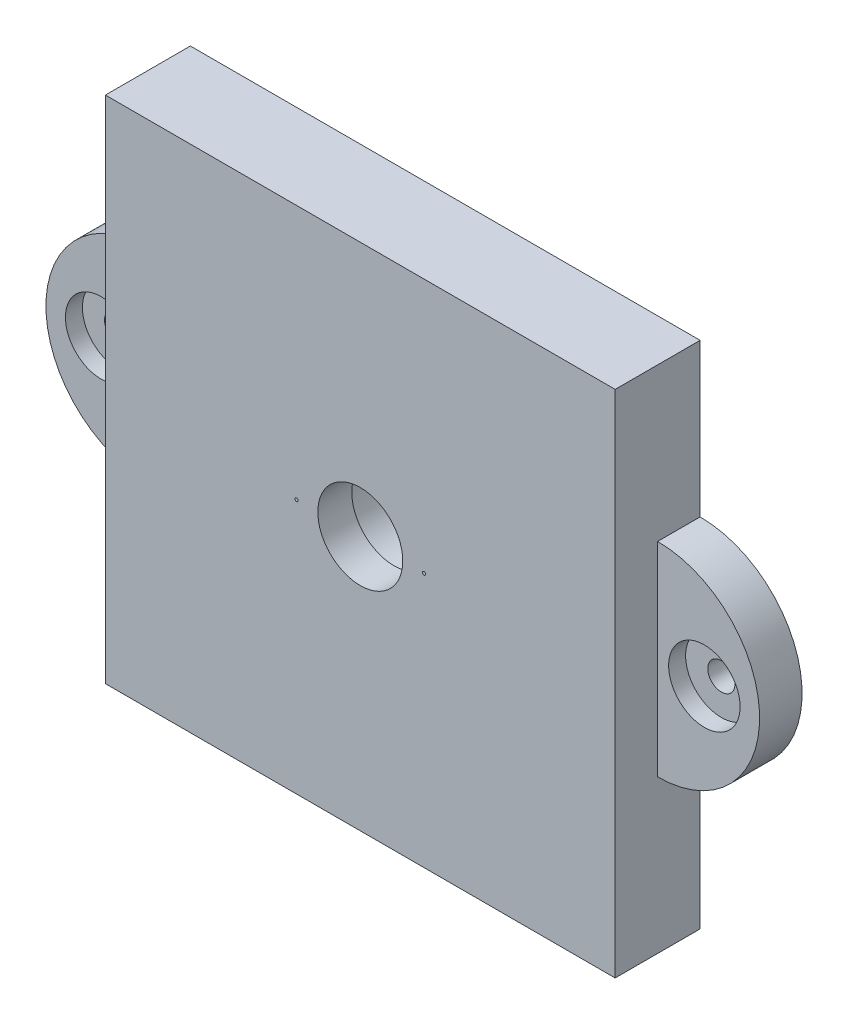
SolidWorks part; units mm, degrees
ref_plane "Plan de face" through (0, 0, 0) normal (0, 0, 1) x (1, 0, 0)
ref_plane "Plan de dessus" through (0, 0, 0) normal (0, 1, 0) x (1, 0, 0)
ref_plane "Plan de droite" through (0, 0, 0) normal (1, 0, 0) x (0, 0, -1)
sketch "Esquisse1" plane through (0, 0, 0) normal (0, 0, 1) x (1, 0, 0)
  line L1 (-30.7513, 21.8422) -> (1.2487, 21.8422)
  line L2 (-30.7513, 21.8422) -> (-30.7513, 3.8422)
  line L3 (-30.7513, -38.1578) -> (29.2487, -38.1578)
  line L4 (29.2487, 21.8422) -> (29.2487, 3.8422)
  line L5 (1.2487, 21.8422) -> (29.2487, 21.8422)
  line L8 (29.2487, -20.1578) -> (29.2487, -38.1578)
  line L9 (-30.7513, -20.1578) -> (-30.7513, -38.1578)
  arc A1 (29.2487, 3.8422) -> (29.2487, -20.1578) centre (29.2487, -8.1578) cw
  arc A2 (-30.7513, -20.1578) -> (-30.7513, 3.8422) centre (-30.7513, -8.1578) cw
  dimension "D3" = 18
  dimension "D7" = 12
  dimension "D4" = 12
  dimension "D1" = 60
  dimension "D2" = 60
  dimension "D5" = 18
  dimension "D6" = 28
extrude "Boss.-Extru.1" add sketch "Esquisse1" along normal blind 10
sketch "Esquisse2" plane through (0, 0, 10) normal (0, 0, 1) x (1, 0, 0)
  line L5 (29.2487, 21.8422) -> (-30.7513, 21.8422) construction
  line L10 (29.2487, -38.1578) -> (29.2487, -20.1578) construction
  circle A0 centre (-0.7513, -8.1578) radius 5
  dimension "D1" = 30
  dimension "D2" = 30
  dimension "D3" = 10
extrude "Enlèv. mat.-Extru.1" cut sketch "Esquisse2" against normal through all
ref_plane "Plan1" through (-0.7513, 0, 0) normal (-1, 0, 0) x (0, 0, 1)
ref_plane "Plan2" through (0, -8.1578, 0) normal (0, 1, 0) x (1, 0, 0)
hole_wizard "Chambrage pour vis à tête hexagonale M4 (Grade A)1" positions "Esquisse6" profile "Esquisse7" counterbore size "M4" standard "KS"
sketch "Esquisse6" plane through (0, 0, 10) normal (0, 0, 1) x (1, 0, 0)
  line L0 (29.2487, 3.8422) -> (29.2487, 21.8422) construction
  line L1 (-30.7513, 21.8422) -> (-30.7513, 3.8422) construction
  point P0 (-35.2513, -3.1578)
  point P4 (33.7487, -3.1578)
  dimension "D1" = 4.5
  dimension "D2" = 4.5
sketch "Esquisse7" plane through (-35.2513, -3.1578, 10) normal (1, 0, 0) x (0, -1, 0)
  line L0 (0, 0) -> (0, 10)
  line L1 (0, 10) -> (2.4, 10)
  line L3 (2.4, 10) -> (2.4, 2.8)
  line L4 (2.4, 2.8) -> (5.3525, 2.8)
  line L5 (5.3525, 2.8) -> (5.3525, 0)
  line L7 (5.3525, 0) -> (0, 0)
  line L11 (0, -6.35) -> (0, 107.95) construction
  dimension "Diamètre du perçage jusqu'au prochain" = 4.8
  dimension "Profondeur du perçage jusqu'au prochain" = 10
  dimension "Diamètre du chambrage" = 10.705
  dimension "Profondeur du chambrage" = 2.8
sketch "Esquisse13" plane through (0, 0, 0) normal (0, 0, -1) x (-1, 0, 0)
  line L0 (-29.2487, 21.8422) -> (30.7513, 21.8422) construction
  line L1 (-27.2487, 19.8422) -> (28.7513, 19.8422)
  line L2 (-27.2487, 19.8422) -> (-27.2487, -36.1578)
  line L3 (-27.2487, -36.1578) -> (28.7513, -36.1578)
  line L4 (28.7513, 19.8422) -> (28.7513, -36.1578)
  line L5 (30.7513, -38.1578) -> (-29.2487, -38.1578) construction
  line L6 (-29.2487, -38.1578) -> (-29.2487, -20.1578) construction
  line L7 (30.7513, 21.8422) -> (30.7513, 3.8422) construction
  dimension "D1" = 2
  dimension "D2" = 2
  dimension "D3" = 2
  dimension "D4" = 2
extrude "Enlèv. mat.-Extru.5" cut sketch "Esquisse13" against normal blind 6
hole_wizard "Dégagement M3.52" positions "Esquisse14" profile "Esquisse15" hole size "M3.5" standard "KS"
sketch "Esquisse14" plane through (0, 0, 6) normal (0, 0, -1) x (-1, 0, 0)
  line L0 (20.2585, -8.1578) -> (-20.2585, -8.1578) construction
  circle A0 centre (0.7513, -8.1578) radius 5 construction
  point P0 (8.2513, -8.1578)
  point P4 (-6.7487, -8.1578)
  dimension "D1" = 15
  dimension "D2" = 7.5
sketch "Esquisse15" plane through (-8.2513, -8.1578, 6) normal (1, 0, 0) x (0, 1, 0)
  line L0 (0, 0) -> (0, 4.1116)
  line L1 (0, 4.1116) -> (1.85, 3)
  line L2 (1.85, 3) -> (1.85, 0)
  line L5 (1.85, 0) -> (0, 0)
  line L10 (0, 4.1116) -> (-1.85, 3) construction
  line L11 (0, -6.35) -> (0, 107.95) construction
  dimension "Diamètre du perçage" = 3.7
  dimension "Profondeur du perçage" = 3
  dimension "Angle de pointe" = 118
sketch "Esquisse16" plane through (0, 0, 10) normal (0, 0, 1) x (1, 0, 0)
  line L0 (-30.7513, -20.1578) -> (-30.7513, -38.1578) construction
  line L1 (-30.7513, 3.8422) -> (-47.0482, 3.8422)
  line L2 (-30.7513, 3.8422) -> (-30.7513, -23.8046)
  line L3 (-30.7513, -23.8046) -> (-47.0482, -23.8046)
  line L4 (-47.0482, 3.8422) -> (-47.0482, -23.8046)
  line L5 (29.2487, 3.8422) -> (61.6332, 3.8422)
  line L6 (29.2487, 3.8422) -> (29.2487, -25.2677)
  line L7 (29.2487, -25.2677) -> (61.6332, -25.2677)
  line L8 (61.6332, 3.8422) -> (61.6332, -25.2677)
  line L9 (29.2487, -38.1578) -> (29.2487, -20.1578) construction
extrude "Enlèv. mat.-Extru.6" cut sketch "Esquisse16" against normal blind 5
hole_wizard "Chambrage pour vis à tête hexagonale M3 (Grade A)1" positions "Esquisse17" profile "Esquisse18" counterbore size "M3" standard "KS" end condition through all
sketch "Esquisse17" plane through (0, 0, 5) normal (0, 0, 1) x (1, 0, 0)
  line L0 (20.2585, -8.1578) -> (-20.2585, -8.1578) construction
  line L2 (29.2487, -38.1578) -> (29.2487, 21.8422) construction
  line L3 (-30.7513, 21.8422) -> (-30.7513, -38.1578) construction
  point P0 (34.7487, -8.1578)
  point P4 (-36.2513, -8.1578)
  dimension "D1" = 5.5
  dimension "D2" = 5.5
sketch "Esquisse18" plane through (34.7487, -8.1578, 5) normal (1, 0, 0) x (0, -1, 0)
  line L0 (0, 0) -> (0, 5)
  line L1 (0, 5) -> (1.6, 5)
  line L3 (1.6, 5) -> (1.6, 2)
  line L4 (1.6, 2) -> (4.206, 2)
  line L5 (4.206, 2) -> (4.206, 0)
  line L7 (4.206, 0) -> (0, 0)
  line L11 (0, -6.35) -> (0, 107.95) construction
  dimension "Diamètre du perçage jusqu'au prochain" = 3.2
  dimension "Profondeur du perçage jusqu'au prochain" = 5
  dimension "Diamètre du chambrage" = 8.412
  dimension "Profondeur du chambrage" = 2
sketch "Sketch1" plane through (0, 0, 6) normal (0, 0, -1) x (-1, 0, 0)
  line L2 (-13.2487, -0.1578) -> (-13.2487, -16.1578)
  line L3 (-13.2487, -16.1578) -> (14.7513, -16.1578)
  line L4 (14.7513, -0.1578) -> (14.7513, -16.1578)
  line L9 (-13.2487, -0.1578) -> (14.7513, -0.1578)
  line L10 (-27.2487, -36.1578) -> (28.7513, -36.1578) construction
  line L12 (28.7513, 19.8422) -> (-27.2487, 19.8422) construction
  line L13 (28.7513, -36.1578) -> (28.7513, 19.8422) construction
  line L14 (-27.2487, 19.8422) -> (-27.2487, -36.1578) construction
  circle A0 centre (-6.7487, -8.1578) radius 1.85
  circle A1 centre (8.2513, -8.1578) radius 1.85
  circle A2 centre (0.7513, -8.1578) radius 5.5
  circle A3 centre (-6.7487, -8.1578) radius 1.85 construction
  circle A4 centre (8.2513, -8.1578) radius 1.85 construction
  dimension "D1" = 20
  dimension "D2" = 20
  dimension "D3" = 14
  dimension "D4" = 14
extrude "Boss-Extrude1" add sketch "Sketch1" along normal blind 8
